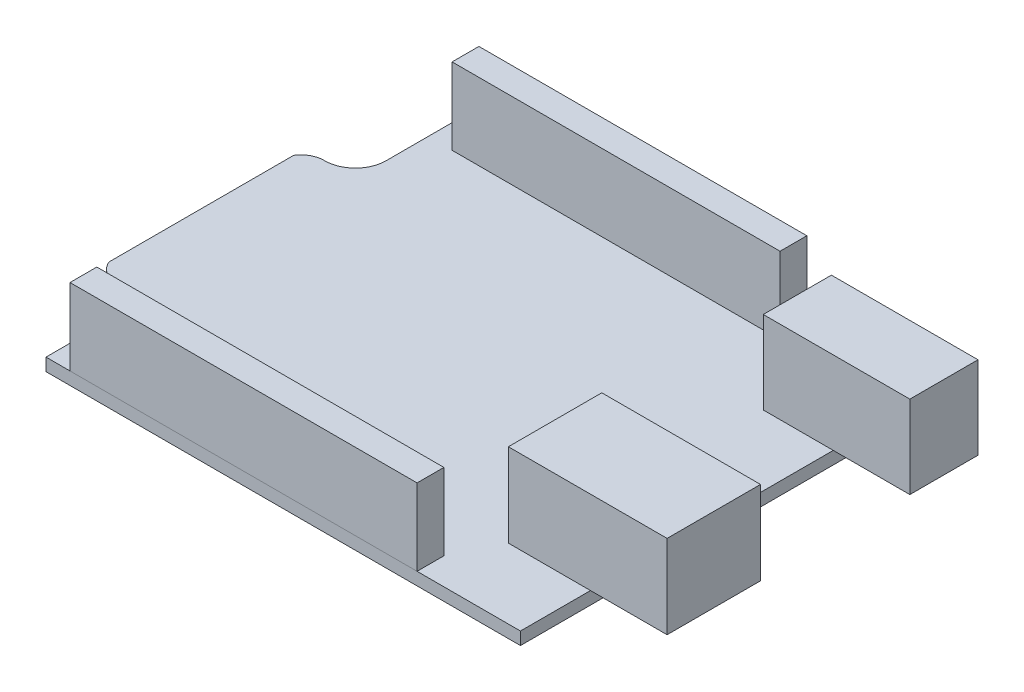
SolidWorks part; units mm, degrees
ref_plane "Front Plane" through (0, 0, 0) normal (0, 0, 1) x (1, 0, 0)
ref_plane "Top Plane" through (0, 0, 0) normal (0, 1, 0) x (1, 0, 0)
ref_plane "Right Plane" through (0, 0, 0) normal (1, 0, 0) x (0, 0, -1)
sketch "Sketch1" plane through (0, 0, 0) normal (0, 1, 0) x (1, 0, 0)
  line L1 (-34.3, -26.7) -> (34.3, -26.7)
  line L2 (-34.3, -26.7) -> (-34.3, 26.7)
  line L3 (-34.3, 26.7) -> (34.3, 26.7)
  line L4 (34.3, -26.7) -> (34.3, 26.7)
  line L5 (-34.3, -26.7) -> (34.3, 26.7) construction
  line L6 (-34.3, 26.7) -> (34.3, -26.7) construction
  point P0 (0, 0)
  dimension "D1" = 53.4
  dimension "D2" = 68.6
extrude "Boss-Extrude1" add sketch "Sketch1" along normal blind 11.65
sketch "Sketch2" plane through (0, 11.65, 0) normal (0, 1, 0) x (1, 0, 0)
  line L0 (-27.6543, -26.7) -> (-27.6543, -17.7)
  line L1 (-34.3, -26.7) -> (34.3, -26.7) construction
  line L2 (-34.3, 26.7) -> (-34.3, -26.7) construction
  line L3 (34.3, 26.7) -> (-34.3, 26.7) construction
  line L4 (-27.6543, 26.7) -> (-27.6543, 17.7)
  line L5 (-34.3, -9.5811) -> (-34.3, -26.7)
  line L6 (-34.3, -26.7) -> (-27.6543, -26.7)
  line L7 (-34.3, 12.2799) -> (-34.3, 26.7)
  line L8 (-34.3, 26.7) -> (-27.6543, 26.7)
  arc A0 (-27.6543, -17.7) -> (-31.5759, -13.7008) centre (-31.6543, -17.7) ccw
  arc A1 (-31.5759, -13.7008) -> (-34.3, -9.5811) centre (-31.517, -10.7013) cw
  arc A2 (-27.6543, 17.7) -> (-31.7086, 13.7004) centre (-31.6543, 17.7) cw
  arc A3 (-31.7086, 13.7004) -> (-34.3, 12.2799) centre (-31.7493, 10.7006) ccw
  line M6 (-34.3, -26.7) -> (34.3, -26.7)
  dimension "D3" = 4
  dimension "D4" = 4
  dimension "D5" = 3
  dimension "D6" = 3
  dimension "D1" = 9
  dimension "D2" = 9
extrude "Cut-Extrude1" cut sketch "Sketch2" against normal blind 11.65 contours A0 A1 L5 L0 M6 | A2 A3 L7 L8 L4
sketch "Sketch3" plane through (0, 11.65, 0) normal (0, 1, 0) x (1, 0, 0)
  line L8 (34.3, -26.7) -> (34.3, 26.7) construction
  line L10 (34.3, 11.2492) -> (18.3, 11.2492) construction
  line L11 (18.3, 11.2492) -> (18.3, 23.1992) construction
  line L13 (34.3, 26.7) -> (-27.6543, 26.7) construction
  line L14 (18.3, 23.1992) -> (34.3, 23.1992) construction
  line L26 (-27.6543, -26.7) -> (34.3, -26.7) construction
  line L31 (-24.5219, -23.1969) -> (-24.5219, -26.7)
  line L35 (-24.5219, 23.1992) -> (-24.5219, 26.7)
  line L36 (18.3, 23.1992) -> (-24.5219, 23.1992)
  line L37 (-24.5219, -23.1969) -> (20.8, -23.1969)
  line L38 (20.8, -23.1969) -> (20.8, -26.7)
  line L39 (18.3, 23.1992) -> (18.3, 26.7)
  line L43 (34.3, 11.2492) -> (34.3, 23.1992) construction
  line L45 (20.8, -26.7) -> (-24.5219, -26.7)
  line L47 (-24.5219, 26.7) -> (18.3, 26.7)
  dimension "D1" = 16
  dimension "D3" = 11.95
sketch "Sketch7" plane through (0, 11.65, 0) normal (0, 1, 0) x (1, 0, 0)
  line L6 (-27.6543, -17.7) -> (-27.6543, -26.7)
  line L7 (-27.6543, -26.7) -> (34.3, -26.7)
  line L8 (34.3, -26.7) -> (34.3, 26.7)
  line L9 (34.3, 26.7) -> (-27.6543, 26.7)
  line L10 (-27.6543, 26.7) -> (-27.6543, 17.7)
  line L11 (-34.3, 12.2799) -> (-34.3, -11.8216)
  line L12 (-27.6543, -17.7) -> (-27.6543, -26.7)
  line L13 (-27.6543, -26.7) -> (34.3, -26.7)
  line L14 (34.3, -26.7) -> (34.3, 26.7)
  line L15 (34.3, 26.7) -> (-27.6543, 26.7)
  line L16 (-27.6543, 26.7) -> (-27.6543, 17.7)
  line L17 (-34.3, 12.2799) -> (-34.3, -11.8216)
  arc A4 (-27.6543, -17.7) -> (-31.5759, -13.7008) centre (-31.6543, -17.7) ccw
  arc A5 (-31.7086, 13.7004) -> (-27.6543, 17.7) centre (-31.6543, 17.7) ccw
  arc A6 (-31.7086, 13.7004) -> (-34.3, 12.2799) centre (-31.7493, 10.7006) ccw
  arc A7 (-34.3, -11.8216) -> (-31.5759, -13.7008) centre (-31.517, -10.7013) ccw
  arc A8 (-27.6543, -17.7) -> (-31.5759, -13.7008) centre (-31.6543, -17.7) ccw
  arc A9 (-31.7086, 13.7004) -> (-27.6543, 17.7) centre (-31.6543, 17.7) ccw
  arc A10 (-31.7086, 13.7004) -> (-34.3, 12.2799) centre (-31.7493, 10.7006) ccw
  arc A11 (-34.3, -11.8216) -> (-31.5759, -13.7008) centre (-31.517, -10.7013) ccw
  dimension "D1" = 0
extrude "Cut-Extrude29" cut sketch "Sketch7" against normal blind 10
extrude "Boss-Extrude2" add sketch "Sketch3" against normal blind 10 separate body
sketch "Sketch8" plane through (0, 1.65, 0) normal (0, 1, 0) x (1, 0, 0)
  line L0 (34.3, -26.7) -> (34.3, -17.55) construction
  line L1 (34.3, -26.7) -> (34.3, 26.7) construction
  line L2 (34.3, -5.35) -> (34.3, 14.15) construction
  line L3 (34.3, -17.55) -> (23.5732, -17.55) construction
  line L4 (34.3, -17.55) -> (34.3, -5.35) construction
  line L5 (34.3, -5.35) -> (23.5732, -5.35) construction
  line L6 (23.5732, -17.55) -> (23.5732, -5.35) construction
  line L8 (34.3, 14.15) -> (25.1581, 14.15) construction
  line L9 (34.3, 14.15) -> (34.3, 23.05) construction
  line L10 (34.3, 23.05) -> (25.1581, 23.05) construction
  line L11 (25.1581, 14.15) -> (25.1581, 23.05) construction
  dimension "D1" = 9.15
  dimension "D2" = 12.2
  dimension "D3" = 19.5
  dimension "D4" = 8.9
sketch "Sketch9" plane through (0, 1.65, 0) normal (0, 1, 0) x (1, 0, 0)
  line L1 (23.5732, -17.55) -> (34.3, -17.55)
  line L2 (23.5732, -17.55) -> (23.5732, -5.35)
  line L3 (23.5732, -5.35) -> (34.3, -5.35)
  line L4 (34.3, -17.55) -> (34.3, -5.35)
extrude "Boss-Extrude3" add sketch "Sketch9" along normal blind 10.9
sketch "Sketch10" plane through (34.3, 0, 0) normal (1, 0, 0) x (0, 0, -1)
  line L1 (-17.55, 12.55) -> (-5.35, 12.55)
  line L2 (-17.55, 12.55) -> (-17.55, 1.65)
  line L3 (-17.55, 1.65) -> (-5.35, 1.65)
  line L4 (-5.35, 12.55) -> (-5.35, 1.65)
extrude "Boss-Extrude4" add sketch "Sketch10" along normal blind 10
sketch "Sketch11" plane through (0, 1.65, 0) normal (0, 1, 0) x (1, 0, 0)
  line L1 (25.1581, 14.15) -> (34.3, 14.15)
  line L2 (25.1581, 14.15) -> (25.1581, 23.05)
  line L3 (25.1581, 23.05) -> (34.3, 23.05)
  line L4 (34.3, 14.15) -> (34.3, 23.05)
extrude "Boss-Extrude5" add sketch "Sketch11" along normal blind 10.8
sketch "Sketch12" plane through (34.3, 0, 0) normal (1, 0, 0) x (0, 0, -1)
  line L1 (14.15, 12.45) -> (23.05, 12.45)
  line L2 (14.15, 12.45) -> (14.15, 1.65)
  line L3 (14.15, 1.65) -> (23.05, 1.65)
  line L4 (23.05, 12.45) -> (23.05, 1.65)
extrude "Boss-Extrude6" add sketch "Sketch12" along normal blind 10
